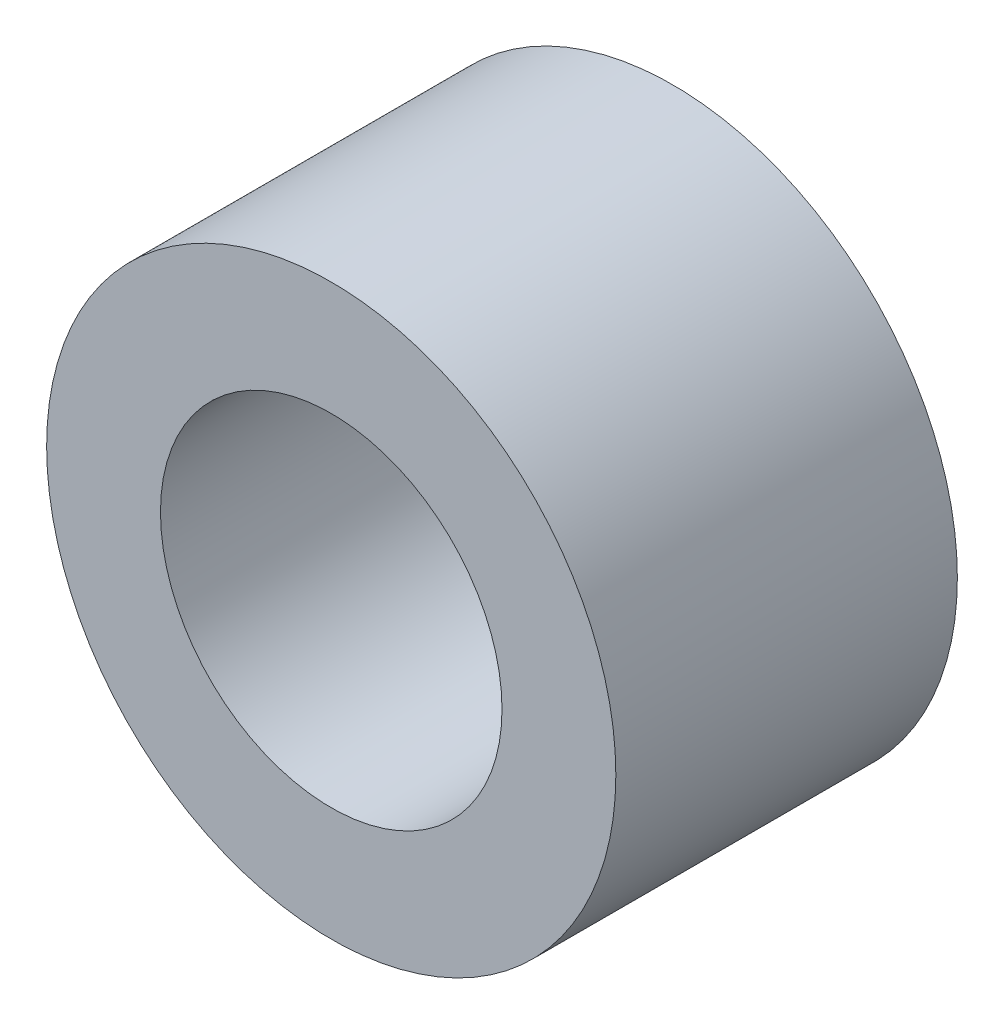
SolidWorks part; units mm, degrees
ref_plane "Front Plane" through (0, 0, 0) normal (0, 0, 1) x (1, 0, 0)
ref_plane "Top Plane" through (0, 0, 0) normal (0, 1, 0) x (1, 0, 0)
ref_plane "Right Plane" through (0, 0, 0) normal (1, 0, 0) x (0, 0, -1)
sketch "Sketch1" plane through (0, 0, 0) normal (0, 0, 1) x (1, 0, 0)
  circle A0 centre (0, 0) radius 2.5
  circle A1 centre (0, 0) radius 1.5
  dimension "D1" = 3
  dimension "D2" = 5
extrude "Boss-Extrude1" add sketch "Sketch1" along normal mid plane 3
